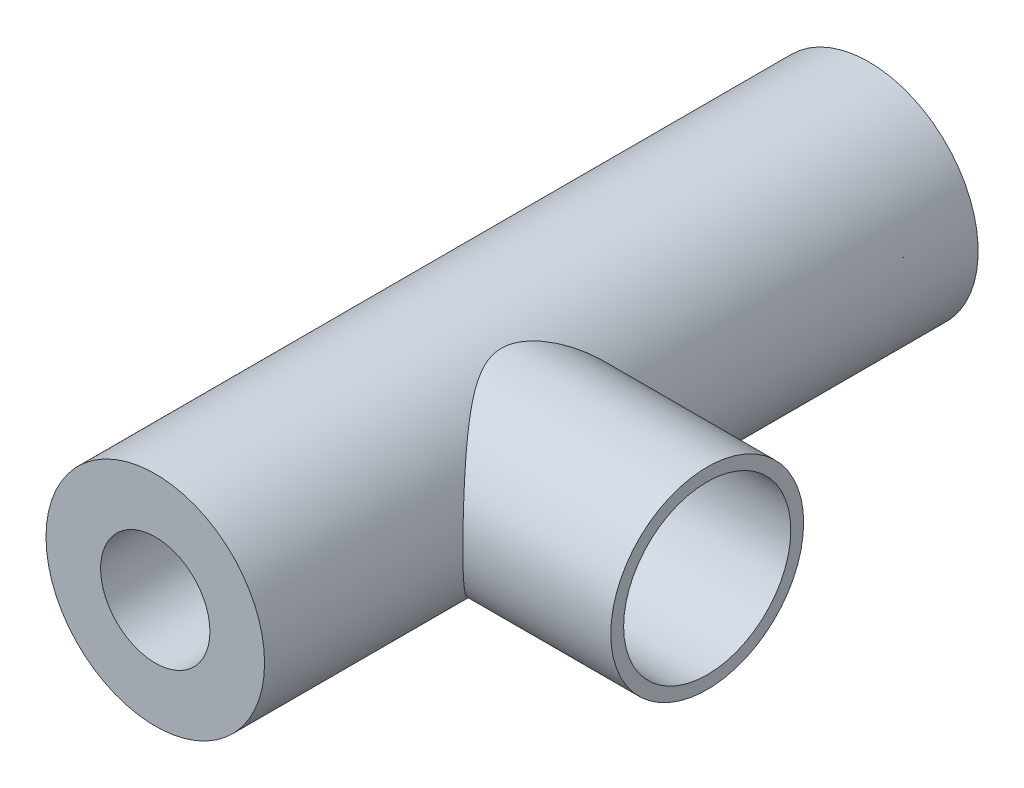
SolidWorks part; units mm, degrees
ref_plane "Front Plane" through (0, 0, 0) normal (0, 0, 1) x (1, 0, 0)
ref_plane "Top Plane" through (0, 0, 0) normal (0, 1, 0) x (1, 0, 0)
ref_plane "Right Plane" through (0, 0, 0) normal (1, 0, 0) x (0, 0, -1)
sketch "Sketch1" plane through (0, 0, 0) normal (0, 0, 1) x (1, 0, 0)
  circle A1 centre (0, 0) radius 17
  dimension "D1" = 34
extrude "Boss-Extrude2" add sketch "Sketch1" along normal blind 40
sketch "Sketch2" plane through (0, 0, 40) normal (0, 0, 1) x (1, 0, 0)
  circle A0 centre (0, 0) radius 8.5
  dimension "D1" = 17
extrude "Cut-Extrude1" cut sketch "Sketch2" against normal blind 38
sketch "Sketch3" plane through (0, 0, 0) normal (0, 0, -1) x (-1, 0, 0)
  circle A0 centre (0, 0) radius 8.5
  dimension "D1" = 17
extrude "Cut-Extrude2" cut sketch "Sketch3" against normal blind 38
sketch "Sketch4" plane through (0, 0, 0) normal (1, 0, 0) x (0, 0, -1)
  line L0 (-48.5184, 0) -> (8.2214, 0) construction
  circle A0 centre (-20.1485, 0) radius 13
  circle A1 centre (-20.1485, 0) radius 15
  dimension "D1" = 30
  dimension "D2" = 26
extrude "Boss-Extrude3" add sketch "Sketch4" along normal blind 40
sketch "Sketch6" plane through (0, 0, 0) normal (0, 0, -1) x (-1, 0, 0)
  circle A0 centre (0, 0) radius 8.5
extrude "Cut-Extrude4" cut sketch "Sketch6" against normal blind 50
sketch "Sketch7" plane through (0, 0, 0) normal (0, 0, -1) x (-1, 0, 0)
  circle A0 centre (0, 0) radius 8.5
  circle A1 centre (0, 0) radius 17
extrude "Boss-Extrude4" add sketch "Sketch7" along normal blind 45
sketch "Sketch8" plane through (0, 0, 40) normal (0, 0, 1) x (1, 0, 0)
  circle A0 centre (0, 0) radius 8.5
  circle A1 centre (0, 0) radius 17
extrude "Boss-Extrude5" add sketch "Sketch8" along normal blind 26
